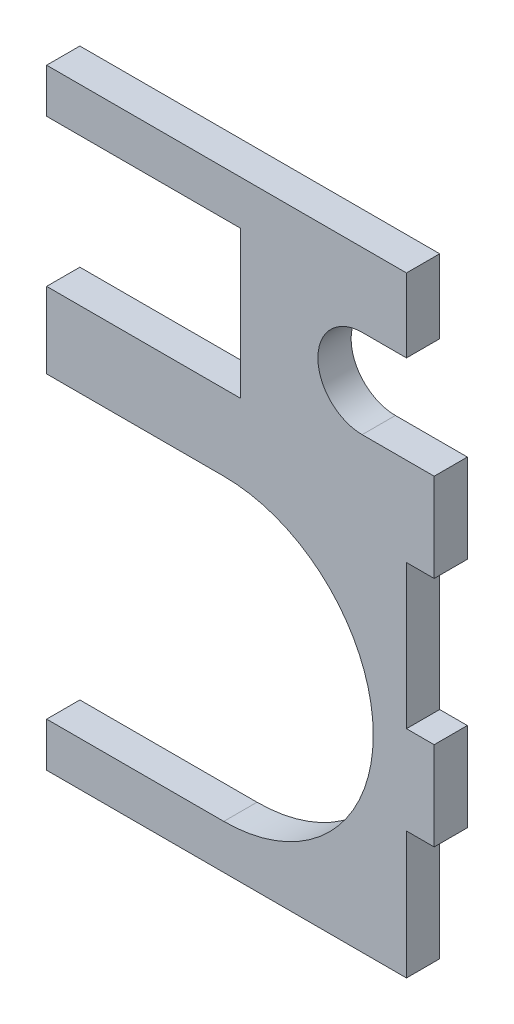
SolidWorks part; units mm, degrees
ref_plane "Plan de face" through (0, 0, 0) normal (0, 0, 1) x (1, 0, 0)
ref_plane "Plan de dessus" through (0, 0, 0) normal (0, 1, 0) x (1, 0, 0)
ref_plane "Plan de droite" through (0, 0, 0) normal (1, 0, 0) x (0, 0, -1)
sketch "Esquisse1" plane through (0, 0, 0) normal (0, 0, 1) x (1, 0, 0)
  line L0 (-16, 33.65) -> (-16, 37.65)
  line L2 (19, 23) -> (19, 15)
  line L3 (19, 2) -> (16.5, 2)
  line L4 (19, 2) -> (19, -6)
  line L5 (19, -6) -> (16.5, -6)
  line L6 (16.5, -17.5) -> (16.5, -6)
  line L7 (-16, -17.5) -> (16.5, -17.5)
  line L8 (-16, -17.5) -> (-16, -13.5)
  line L9 (-16, -13.5) -> (0, -13.5)
  line L10 (0, 13.5) -> (-16, 13.5)
  line L11 (-16, 13.5) -> (-16, 20.35)
  line L12 (16.5, 31) -> (16.5, 37.65)
  line L13 (19, 15) -> (16.5, 15)
  line L14 (16.5, 2) -> (16.5, 15)
  line L15 (-16, 33.65) -> (1.5, 33.65)
  line L16 (1.5, 20.35) -> (-16, 20.35)
  line L17 (16.5, 37.65) -> (-16, 37.65)
  line L19 (12.5, 31) -> (16.5, 31)
  line L20 (12.5, 23) -> (19, 23)
  line L21 (1.5, 33.65) -> (1.5, 20.35)
  arc A0 (12.5, 31) -> (12.5, 23) centre (12.5, 27) ccw
  arc A1 (0, -13.5) -> (0, 13.5) centre (0, 0) ccw
  dimension "D1" = 13.5
  dimension "D2" = 4
  dimension "D3" = 4
  dimension "D4" = 13.3
  dimension "D5" = 6.85
  dimension "D6" = 17.5
  dimension "D7" = 4
  dimension "D8" = 32.5
  dimension "D9" = 2.5
  dimension "D10" = 13
  dimension "D11" = 8
  dimension "D12" = 8
  dimension "D13" = 11.5
  dimension "D14" = 16.5
  dimension "D15" = 4
extrude "Boss.-Extru.1" add sketch "Esquisse1" along normal blind 3
